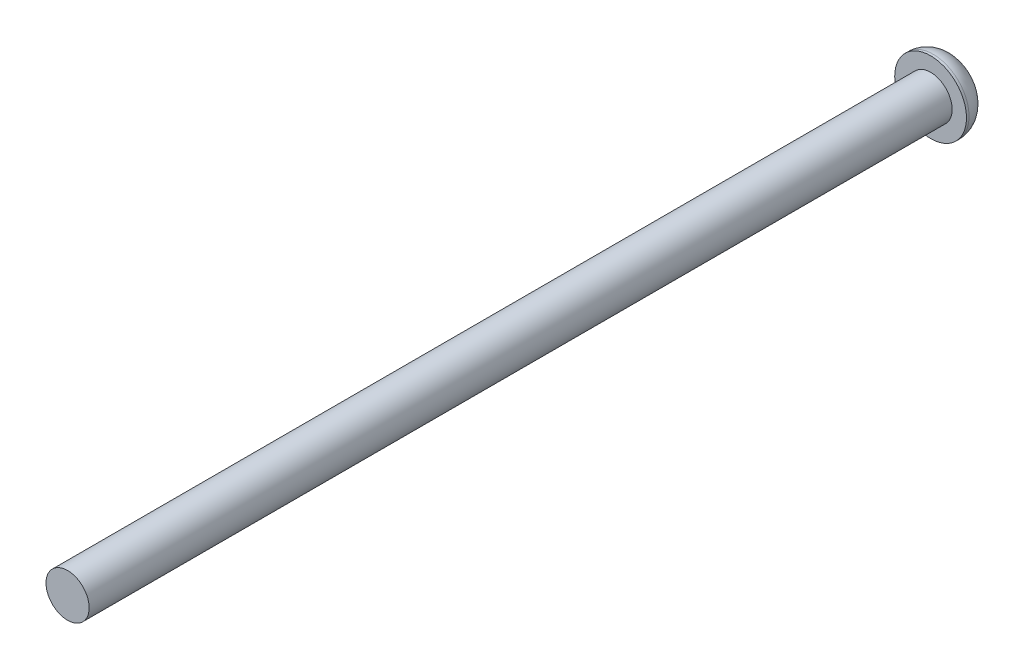
SolidWorks part; units mm, degrees
ref_plane "Front Plane" through (0, 0, 0) normal (0, 0, 1) x (1, 0, 0)
ref_plane "Top Plane" through (0, 0, 0) normal (0, 1, 0) x (1, 0, 0)
ref_plane "Right Plane" through (0, 0, 0) normal (1, 0, 0) x (0, 0, -1)
sketch "Sketch1" plane through (0, 0, 0) normal (0, 0, 1) x (1, 0, 0)
  circle A0 centre (0, 0) radius 2.5
  dimension "D1" = 5
extrude "Boss-Extrude1" add sketch "Sketch1" along normal blind 100
sketch "Sketch2" plane through (0, 0, 0) normal (0, 0, -1) x (-1, 0, 0)
  circle A0 centre (0, 0) radius 4.1596
extrude "Boss-Extrude2" add sketch "Sketch2" along normal blind 2.8
fillet "Fillet1" radius 2.5 1 edges at (-4.1596, 0, -2.8)
sketch "Sketch3" plane through (0, 0, -2.8) normal (0, 0, -1) x (-1, 0, 0)
  line L1 (1.3924, -0.6365) -> (1.2475, 0.8876)
  line L2 (1.2475, 0.8876) -> (-0.145, 1.5241)
  line L3 (-0.145, 1.5241) -> (-1.3924, 0.6365)
  line L4 (-1.3924, 0.6365) -> (-1.2475, -0.8876)
  line L5 (-1.2475, -0.8876) -> (0.145, -1.5241)
  line L6 (0.145, -1.5241) -> (1.3924, -0.6365)
  circle A0 centre (0, 0) radius 1.3259 construction
extrude "Cut-Extrude1" cut sketch "Sketch3" against normal blind 2
